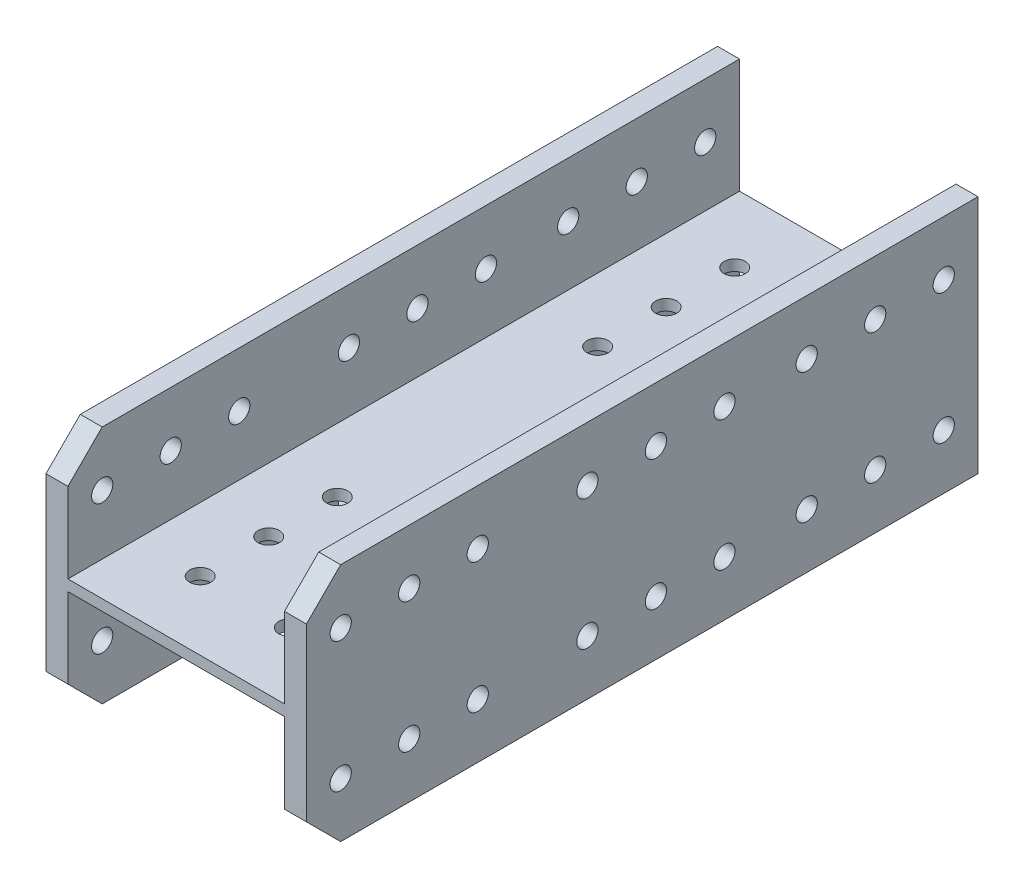
SolidWorks part; units mm, degrees
ref_plane "前视基准面" through (0, 0, 0) normal (0, 0, 1) x (1, 0, 0)
ref_plane "上视基准面" through (0, 0, 0) normal (0, 1, 0) x (1, 0, 0)
ref_plane "右视基准面" through (0, 0, 0) normal (1, 0, 0) x (0, 0, -1)
sketch "草图1" plane through (0, 0, 0) normal (0, 0, 1) x (1, 0, 0)
  line L0 (-1000, 0) -> (49000, 0) construction
  line L1 (0, -1000) -> (0, 49000) construction
  line L3 (-190, 175) -> (190, 175)
  line L4 (-190, 175) -> (-190, -175)
  line L5 (-190, -175) -> (190, -175)
  line L6 (190, 175) -> (190, -175)
  line L7 (-158, 175) -> (158, 175)
  line L8 (-158, 175) -> (-158, 8)
  line L9 (-158, 8) -> (158, 8)
  line L10 (158, 175) -> (158, 8)
  line L11 (-158, -8) -> (158, -8)
  line L12 (-158, -8) -> (-158, -175)
  line L13 (-158, -175) -> (158, -175)
  line L14 (158, -8) -> (158, -175)
  dimension "D1" = 16
  dimension "D2" = 8
  dimension "D3" = 350
  dimension "D4" = 175
  dimension "D5" = 190
  dimension "D6" = 32
  dimension "D7" = 32
  dimension "D8" = 380
extrude "拉伸1" add sketch "草图1" along normal blind 980 contours L11 L14 L5 L6 L3 L10 L9 L8 L4 L12
sketch "草图2" plane through (190, 0, 0) normal (1, 0, 0) x (0, 0, -1)
  line L0 (-1980, 0) -> (48020, 0) construction
  line L1 (-980, 175) -> (-980, -175) construction
  line L2 (-490, -825) -> (-490, 49175) construction
  line L3 (-980, 175) -> (0, 175) construction
  line L4 (-930, 95) -> (-570, 95) construction
  line L5 (-370, 95) -> (-50, 95) construction
  circle A0 centre (-930, 95) radius 15.5
  circle A1 centre (-830, 95) radius 15.5
  circle A2 centre (-730, 95) radius 15.5
  circle A3 centre (-930, -95) radius 15.5
  circle A4 centre (-830, -95) radius 15.5
  circle A5 centre (-730, -95) radius 15.5
  circle A6 centre (-570, 95) radius 15.5
  circle A7 centre (-470, 95) radius 15.5
  circle A8 centre (-370, 95) radius 15.5
  circle A9 centre (-370, -95) radius 15.5
  circle A10 centre (-470, -95) radius 15.5
  circle A11 centre (-570, -95) radius 15.5
  circle A12 centre (-50, 95) radius 15.5
  circle A13 centre (-150, 95) radius 15.5
  circle A14 centre (-250, 95) radius 15.5
  circle A15 centre (-250, -95) radius 15.5
  circle A16 centre (-150, -95) radius 15.5
  circle A17 centre (-50, -95) radius 15.5
  point P5 (-980, 0)
  point P10 (-490, 175)
  dimension "D1" = 31
  dimension "D2" = 95
  dimension "D3" = 50
  dimension "D4" = 190
  dimension "D5" = 100
  dimension "D6" = 360
  dimension "D7" = 320
extrude "拉伸2" cut sketch "草图2" against normal through all
sketch "草图3" plane through (0, 8, 0) normal (0, 1, 0) x (1, 0, 0)
  line L0 (0, -1000) -> (0, 49000) construction
  line L1 (-1190, -490) -> (48810, -490) construction
  line L2 (-190, -980) -> (-190, 0) construction
  line L3 (-158, 0) -> (158, 0) construction
  line L4 (65, -100) -> (-65, -100) construction
  line L5 (-65, -100) -> (-65, -680) construction
  circle A0 centre (65, -100) radius 15.5
  circle A1 centre (-65, -100) radius 15.5
  circle A2 centre (65, -200) radius 15.5
  circle A3 centre (-65, -200) radius 15.5
  circle A4 centre (65, -300) radius 15.5
  circle A5 centre (-65, -300) radius 15.5
  circle A6 centre (-65, -680) radius 15.5
  circle A7 centre (-65, -780) radius 15.5
  circle A8 centre (65, -780) radius 15.5
  circle A9 centre (65, -880) radius 15.5
  circle A10 centre (-65, -880) radius 15.5
  circle A11 centre (65, -680) radius 15.5
  point P8 (-190, -490)
  dimension "D3" = 31
  dimension "D1" = 65
  dimension "D2" = 100
  dimension "D4" = 130
  dimension "D5" = 100
  dimension "D6" = 580
extrude "拉伸3" cut sketch "草图3" against normal through all
sketch "草图4" plane through (190, 0, 0) normal (1, 0, 0) x (0, 0, -1)
  line L0 (-930, 175) -> (-980, 125)
  line L1 (-980, 175) -> (0, 175) construction
  line L2 (-980, 175) -> (-980, -175) construction
  line L3 (-980, 125) -> (-980, 175)
  line L4 (-980, 175) -> (-930, 175)
  line L5 (-980, -125) -> (-930, -175)
  line L6 (-980, -175) -> (0, -175) construction
  line L7 (-930, -175) -> (-980, -175)
  line L8 (-980, -175) -> (-980, -125)
  dimension "D1" = 50
  dimension "D2" = 50
  dimension "D3" = 50
  dimension "D4" = 50
extrude "拉伸4" cut sketch "草图4" against normal through all
